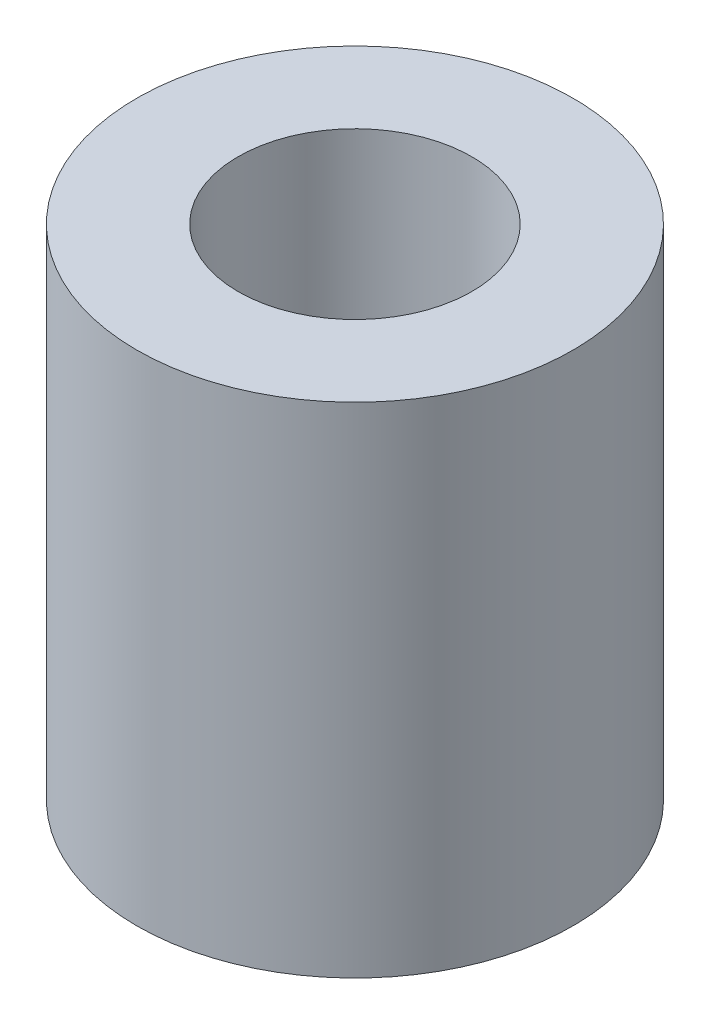
SolidWorks part; units mm, degrees
ref_plane "Front" through (0, 0, 0) normal (0, 0, 1) x (1, 0, 0)
ref_plane "Top" through (0, 0, 0) normal (0, 1, 0) x (1, 0, 0)
ref_plane "Right" through (0, 0, 0) normal (1, 0, 0) x (0, 0, -1)
sketch "Croquis1" plane through (0, 0, 0) normal (0, 1, 0) x (1, 0, 0)
  circle A0 centre (0, 0) radius 3.5
  circle A1 centre (0, 0) radius 1.875
  dimension "D1" = 7
  dimension "D2" = 3.75
extrude "Saliente-Extruir1" add sketch "Croquis1" along normal blind 8
